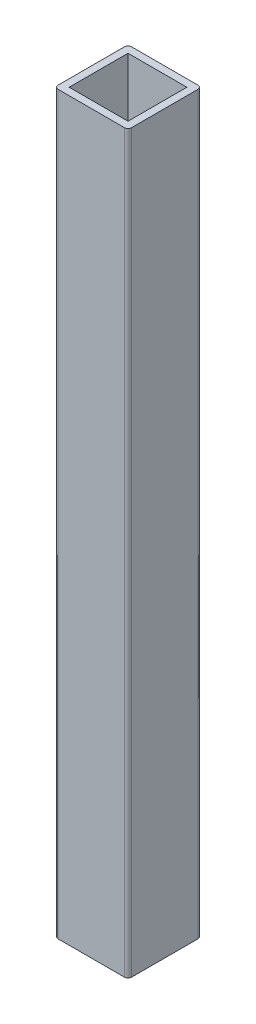
SolidWorks part; units mm, degrees
ref_plane "Front Plane" through (0, 0, 0) normal (0, 0, 1) x (1, 0, 0)
ref_plane "Top Plane" through (0, 0, 0) normal (0, 1, 0) x (1, 0, 0)
ref_plane "Right Plane" through (0, 0, 0) normal (1, 0, 0) x (0, 0, -1)
sketch "Sketch1" plane through (0, 0, 0) normal (0, 1, 0) x (1, 0, 0)
  line L0 (-7.1566, 6.1928) -> (-7.1566, -9.8072)
  line L1 (-9.1566, 8.1928) -> (10.8434, 8.1928)
  line L2 (-9.1566, 8.1928) -> (-9.1566, -11.8072)
  line L3 (-9.1566, -11.8072) -> (10.8434, -11.8072)
  line L4 (10.8434, 8.1928) -> (10.8434, -11.8072)
  line L5 (-7.1566, -9.8072) -> (8.8434, -9.8072)
  line L6 (8.8434, 6.1928) -> (8.8434, -9.8072)
  line L7 (-7.1566, 6.1928) -> (8.8434, 6.1928)
  dimension "D1" = 20
  dimension "D2" = 20
  dimension "D3" = 2
extrude "Boss-Extrude1" add sketch "Sketch1" along normal blind 200
fillet "Fillet1" radius 1 4 edges at (10.8434, 100, -8.1928) (10.8434, 100, 11.8072) (-9.1566, 100, 11.8072) (-9.1566, 100, -8.1928)
